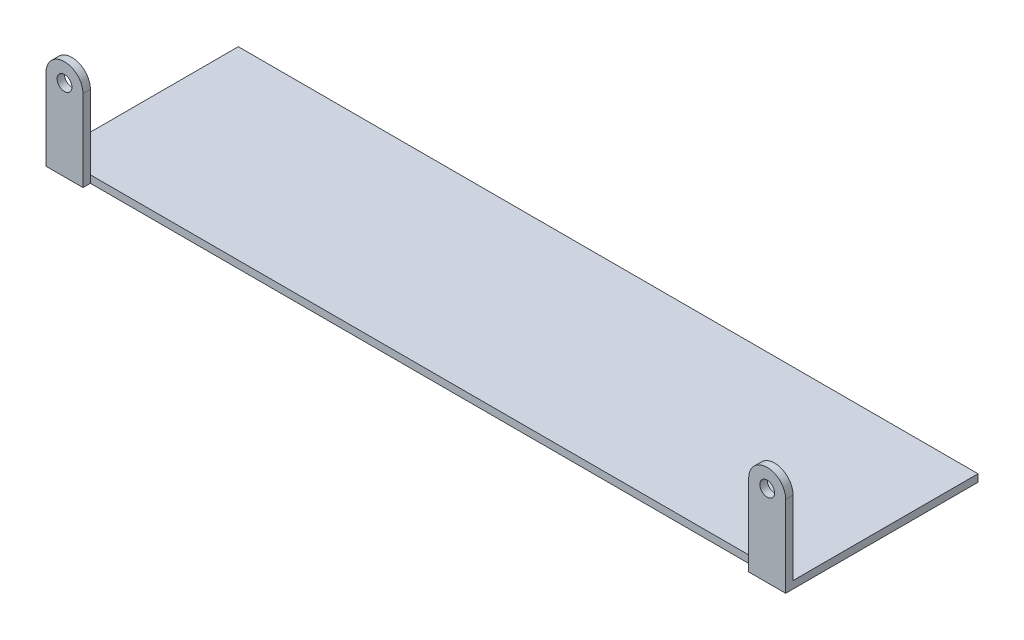
SolidWorks part; units mm, degrees
ref_plane "Front Plane" through (0, 0, 0) normal (0, 0, 1) x (1, 0, 0)
ref_plane "Top Plane" through (0, 0, 0) normal (0, 1, 0) x (1, 0, 0)
ref_plane "Right Plane" through (0, 0, 0) normal (1, 0, 0) x (0, 0, -1)
sketch "Sketch3" plane through (0, 0, 0) normal (0, 1, 0) x (1, 0, 0)
  line L1 (100, -25) -> (-100, -25)
  line L2 (100, -25) -> (100, 25)
  line L3 (100, 25) -> (-100, 25)
  line L4 (-100, -25) -> (-100, 25)
  line L5 (100, -25) -> (-100, 25) construction
  line L6 (100, 25) -> (-100, -25) construction
  point P0 (0, 0)
  dimension "D1" = 50
  dimension "D2" = 200
extrude "Boss-Extrude2" add sketch "Sketch3" along normal mid plane 2
sketch "Sketch4" plane through (0, 0, 25) normal (0, 0, 1) x (1, 0, 0)
  line L0 (0, 64.5255) -> (0, -62.5091) construction
  line L2 (100, -1) -> (90, -1)
  line L3 (100, -1) -> (100, 21)
  line L5 (90, -1) -> (90, 21)
  line L9 (100, 21) -> (90, 21) construction
  line L10 (-90, -1) -> (-90, 21)
  line L11 (-100, -1) -> (-100, 21)
  line L12 (-100, -1) -> (-90, -1)
  arc A0 (90, 21) -> (100, 21) centre (95, 21) cw
  circle A2 centre (95, 21) radius 2
  circle A3 centre (-95, 21) radius 2
  arc A4 (-90, 21) -> (-100, 21) centre (-95, 21) ccw
  dimension "D3" = 4
  dimension "D1" = 22
  dimension "D2" = 10
extrude "Boss-Extrude3" add sketch "Sketch4" along normal blind 2
